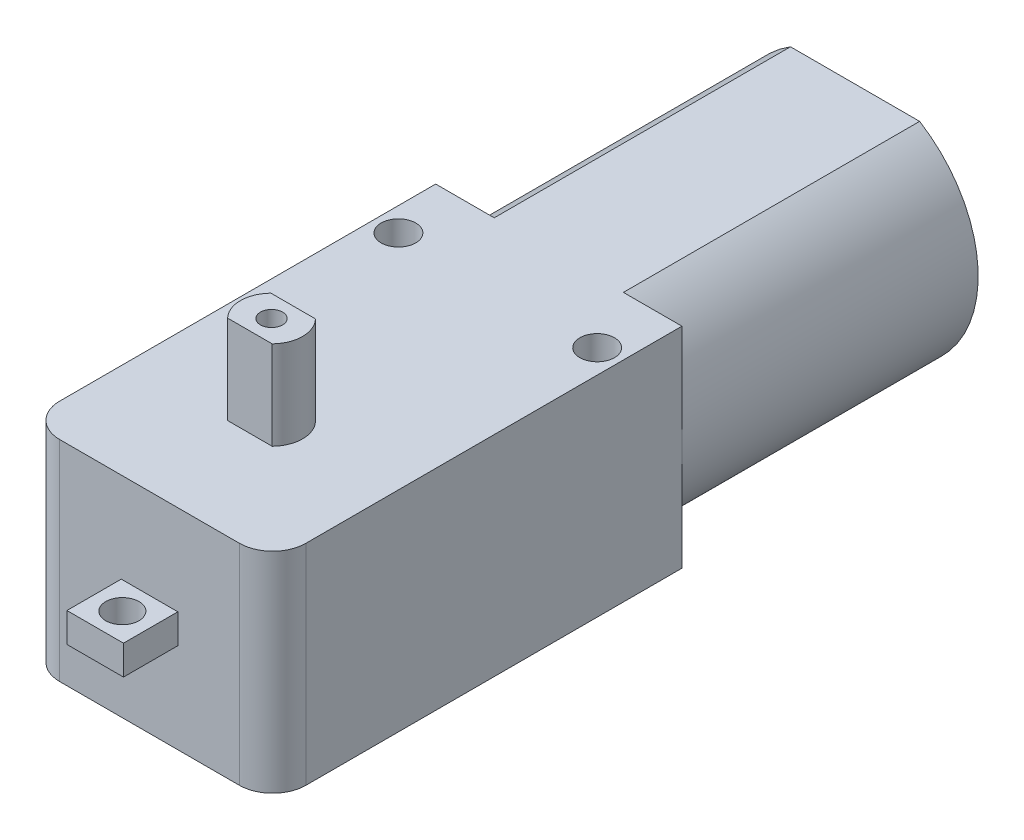
SolidWorks part; units mm, degrees
ref_plane "Front Plane" through (0, 0, 0) normal (0, 0, 1) x (1, 0, 0)
ref_plane "Top Plane" through (0, 0, 0) normal (0, 1, 0) x (1, 0, 0)
ref_plane "Right Plane" through (0, 0, 0) normal (1, 0, 0) x (0, 0, -1)
sketch "Sketch1" plane through (0, 0, 0) normal (0, 0, 1) x (1, 0, 0)
  line L1 (0, 0) -> (22.2, 0)
  line L2 (0, 0) -> (0, 18.9)
  line L3 (0, 18.9) -> (22.2, 18.9)
  line L4 (22.2, 0) -> (22.2, 18.9)
  dimension "D1" = 22.2
  dimension "D2" = 18.9
extrude "Boss-Extrude1" add sketch "Sketch1" against normal blind 36.9
sketch "Sketch2" plane through (0, 0, 0) normal (0, 0, 1) x (1, 0, 0)
  line L0 (11.1, 18.9) -> (11.1, 0) construction
  line L1 (22.2, 18.9) -> (0, 18.9) construction
  line L2 (0, 0) -> (22.2, 0) construction
  line L3 (0, 9.45) -> (22.2, 9.45) construction
  line L4 (0, 18.9) -> (0, 0) construction
  line L5 (22.2, 0) -> (22.2, 18.9) construction
  line L7 (8.55, 10.775) -> (13.65, 10.775)
  line L8 (8.55, 10.775) -> (8.55, 8.125)
  line L9 (8.55, 8.125) -> (13.65, 8.125)
  line L10 (13.65, 10.775) -> (13.65, 8.125)
  line L11 (8.55, 10.775) -> (13.65, 8.125) construction
  line L12 (8.55, 8.125) -> (13.65, 10.775) construction
  point P12 (11.1, 9.45)
  dimension "D1" = 5.1
  dimension "D2" = 2.65
extrude "Boss-Extrude2" add sketch "Sketch2" along normal blind 4.9
sketch "Sketch3" plane through (0, 0, -36.9) normal (0, 0, -1) x (-1, 0, 0)
  line L0 (-11.1, 18.9) -> (-11.1, 0) construction
  line L1 (-22.2, 18.9) -> (0, 18.9) construction
  line L2 (0, 0) -> (-22.2, 0) construction
  line L3 (-22.2, 9.45) -> (0, 9.45) construction
  line L4 (-22.2, 0) -> (-22.2, 18.9) construction
  line L5 (0, 18.9) -> (0, 0) construction
  line L6 (-16.923, 18.9) -> (-5.277, 18.9)
  line L7 (-16.923, 0) -> (-5.277, 0)
  arc A0 (-5.277, 0) -> (-5.277, 18.9) centre (-11.1, 9.45) ccw
  arc A1 (-16.923, 18.9) -> (-16.923, 0) centre (-11.1, 9.45) ccw
extrude "Boss-Extrude3" add sketch "Sketch3" along normal blind 26.71
sketch "Sketch4" plane through (0, 0, -63.61) normal (0, 0, -1) x (-1, 0, 0)
  line L0 (-11.1, 18.9) -> (-11.1, 0) construction
  line L1 (-5.277, 18.9) -> (-16.923, 18.9) construction
  line L2 (-16.923, 0) -> (-5.277, 0) construction
  line L3 (-22.2, 9.45) -> (0, 9.45) construction
  arc A0 (-16.923, 18.9) -> (-16.923, 0) centre (-11.1, 9.45) ccw construction
  arc A1 (-5.277, 0) -> (-5.277, 18.9) centre (-11.1, 9.45) ccw construction
  circle A2 centre (-11.1, 9.45) radius 1
  dimension "D1" = 2
extrude "Boss-Extrude4" add sketch "Sketch4" along normal blind 1
sketch "Sketch5" plane through (0, 18.9, 0) normal (0, 1, 0) x (1, 0, 0)
  line L0 (11.1, 0) -> (11.1, 63.61) construction
  line L1 (13.65, 0) -> (8.55, 0) construction
  line L2 (5.277, 63.61) -> (16.923, 63.61) construction
  line L3 (0, 11) -> (22.2, 11) construction
  line L4 (0, 36.9) -> (0, 0) construction
  line L5 (22.2, 36.9) -> (22.2, 0) construction
  line L6 (22.2, 0) -> (0, 0) construction
  line L7 (9.0906, 12.95) -> (13.1094, 12.95)
  line L8 (9.0906, 9.05) -> (13.1094, 9.05)
  arc A0 (9.0906, 12.95) -> (9.0906, 9.05) centre (11.1, 11) ccw
  arc A1 (13.1094, 9.05) -> (13.1094, 12.95) centre (11.1, 11) ccw
  dimension "D2" = 5.6
  dimension "D1" = 11
  dimension "D3" = 1.95
  dimension "D4" = 1.95
extrude "Boss-Extrude5" add sketch "Sketch5" along normal blind 8
sketch "Sketch6" plane through (0, 0, 0) normal (0, -1, 0) x (1, 0, 0)
  line L0 (11.1, 0) -> (11.1, -63.61) construction
  line L1 (8.55, 0) -> (13.65, 0) construction
  line L2 (16.923, -63.61) -> (5.277, -63.61) construction
  line L3 (0, -11) -> (22.2, -11) construction
  line L4 (0, -36.9) -> (0, 0) construction
  line L5 (22.2, -36.9) -> (22.2, 0) construction
  line L6 (0, 0) -> (22.2, 0) construction
  line L7 (9.0906, -9.05) -> (13.1094, -9.05)
  line L8 (9.0906, -12.95) -> (13.1094, -12.95)
  arc A0 (9.0906, -9.05) -> (9.0906, -12.95) centre (11.1, -11) ccw
  arc A1 (13.1094, -12.95) -> (13.1094, -9.05) centre (11.1, -11) ccw
  dimension "D2" = 5.6
  dimension "D1" = 11
  dimension "D3" = 1.95
  dimension "D4" = 1.95
extrude "Boss-Extrude6" add sketch "Sketch6" along normal blind 8 contours L7 A1 L8 A0
sketch "Sketch8" plane through (0, 10.775, 0) normal (0, 1, 0) x (1, 0, 0)
  line L0 (11.1, 0) -> (11.1, -4.9) construction
  line L1 (22.2, 0) -> (0, 0) construction
  line L2 (13.65, -4.9) -> (8.55, -4.9) construction
  line L3 (8.55, -2.45) -> (13.65, -2.45) construction
  line L4 (8.55, -4.9) -> (8.55, 0) construction
  line L5 (13.65, -4.9) -> (13.65, 0) construction
  circle A0 centre (11.1, -2.45) radius 1.5
  dimension "D1" = 3
extrude "Cut-Extrude1" cut sketch "Sketch8" against normal through all
sketch "Sketch9" plane through (0, 26.9, 0) normal (0, 1, 0) x (1, 0, 0)
  line L0 (11.1, 12.95) -> (11.1, 9.05) construction
  line L1 (13.1094, 12.95) -> (9.0906, 12.95) construction
  line L2 (9.0906, 9.05) -> (13.1094, 9.05) construction
  line L3 (8.3, 11) -> (13.9, 11) construction
  arc A0 (9.0906, 12.95) -> (9.0906, 9.05) centre (11.1, 11) ccw construction
  arc A1 (13.1094, 9.05) -> (13.1094, 12.95) centre (11.1, 11) ccw construction
  circle A2 centre (11.1, 11) radius 1
  dimension "D1" = 2
extrude "Cut-Extrude2" cut sketch "Sketch9" against normal through all
sketch "Sketch10" plane through (0, 18.9, 0) normal (0, 1, 0) x (1, 0, 0)
  line L0 (0, 31.4) -> (22.2, 31.4) construction
  line L1 (0, 36.9) -> (0, 0) construction
  line L2 (22.2, 36.9) -> (22.2, 0) construction
  line L3 (5.277, 36.9) -> (0, 36.9) construction
  line L4 (2.14, 31.4) -> (2.14, 36.9) construction
  line L5 (5.277, 36.9) -> (0, 36.9) construction
  line L6 (20.06, 31.4) -> (20.06, 36.9) construction
  line L7 (22.2, 36.9) -> (16.923, 36.9) construction
  circle A0 centre (2.14, 31.4) radius 1.56
  circle A1 centre (20.06, 31.4) radius 1.56
  dimension "D4" = 3.12
  dimension "D5" = 3.12
  dimension "D1" = 5.5
  dimension "D2" = 2.14
  dimension "D3" = 2.14
extrude "Cut-Extrude3" cut sketch "Sketch10" against normal through all
fillet "Fillet1" radius 3 2 edges at (0, 9.45, 0) (22.2, 9.45, 0)
